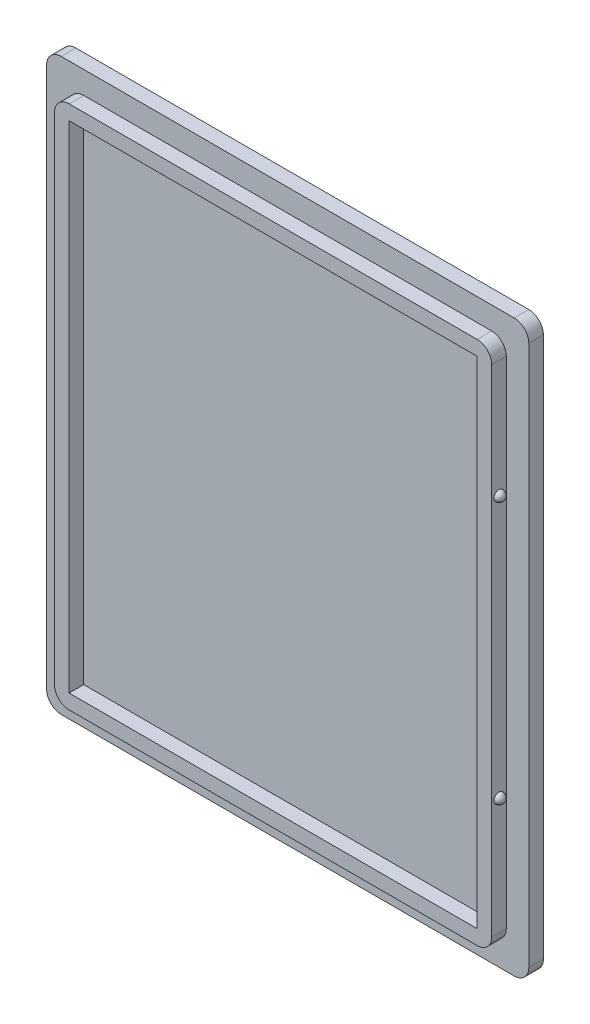
SolidWorks part; units mm, degrees
ref_plane "Plan de face" through (0, 0, 0) normal (1, 0, 0) x (0, 1, 0)
ref_plane "Plan de dessus" through (0, 0, 0) normal (0, 0, 1) x (0, 1, 0)
ref_plane "Plan de droite" through (0, 0, 0) normal (0, 1, 0) x (-1, 0, 0)
sketch "Esquisse1" plane through (0, 0, 0) normal (0, 0, 1) x (0, 1, 0)
  line L1 (-19.5, 16.5) -> (19.5, 16.5)
  line L2 (-19.5, 16.5) -> (-19.5, -16.5)
  line L3 (-19.5, -16.5) -> (19.5, -16.5)
  line L4 (19.5, 16.5) -> (19.5, -16.5)
  line L5 (-19.5, 16.5) -> (19.5, -16.5) construction
  line L6 (-19.5, -16.5) -> (19.5, 16.5) construction
  point P0 (0, 0)
  dimension "D1" = 39
  dimension "D2" = 33
extrude "Boss.-Extru.1" add sketch "Esquisse1" along normal blind 1
sketch "Esquisse2" plane through (0, 0, 1) normal (0, 0, 1) x (1, 0, 0)
  line L0 (-16.5, -19.5) -> (16.5, -19.5) construction
  line L5 (-14.96, 17.96) -> (-14.96, -17.96)
  line L6 (-14.96, -17.96) -> (14.96, -17.96)
  line L7 (14.96, 17.96) -> (14.96, -17.96)
  line L8 (-14.96, 17.96) -> (14.96, 17.96)
  line L9 (16.5, 19.5) -> (-16.5, 19.5) construction
  line L10 (-16.5, 19.5) -> (-16.5, -19.5) construction
  line L11 (16.5, -19.5) -> (16.5, 19.5) construction
  line L12 (-13.96, 16.96) -> (-13.96, -16.96)
  line L13 (-13.96, -16.96) -> (13.96, -16.96)
  line L14 (13.96, 16.96) -> (13.96, -16.96)
  line L15 (-13.96, 16.96) -> (13.96, 16.96)
  dimension "D1" = 1.54
  dimension "D2" = 1.54
  dimension "D3" = 1.54
  dimension "D4" = 1.54
  dimension "D5" = 1
extrude "Boss.-Extru.2" add sketch "Esquisse2" along normal blind 1
sketch "Esquisse3" plane through (14.96, 0, 0) normal (1, 0, 0) x (0, 1, 0)
  line L0 (-17.96, 1.5) -> (17.96, 1.5) construction
  line L1 (-17.96, 2) -> (-17.96, 1) construction
  line L2 (17.96, 2) -> (17.96, 1) construction
  line L3 (-9.31, 1.5) -> (-8.61, 1.5)
  arc A1 (-9.31, 1.5) -> (-8.61, 1.5) centre (-8.96, 1.5) cw
  dimension "D1" = 0.7
  dimension "D2" = 9
revolve "Révolution2" add sketch "Esquisse3" angle 180 about L0
mirror "Symétrie1" about plane through (0, 0, 0) normal (0, 1, 0) of "Révolution2"
mirror "Symétrie2" about plane through (0, 0, 0) normal (1, 0, 0) of "Symétrie1", "Révolution2"
fillet "Congé1" radius 1 4 edges at (16.5, -19.5, 0.5) (-16.5, -19.5, 0.5) (-16.5, 19.5, 0.5) (16.5, 19.5, 0.5)
fillet "Congé2" radius 1 4 edges at (14.96, 17.96, 1.5) (-14.96, 17.96, 1.5) (-14.96, -17.96, 1.5) (14.96, -17.96, 1.5)
